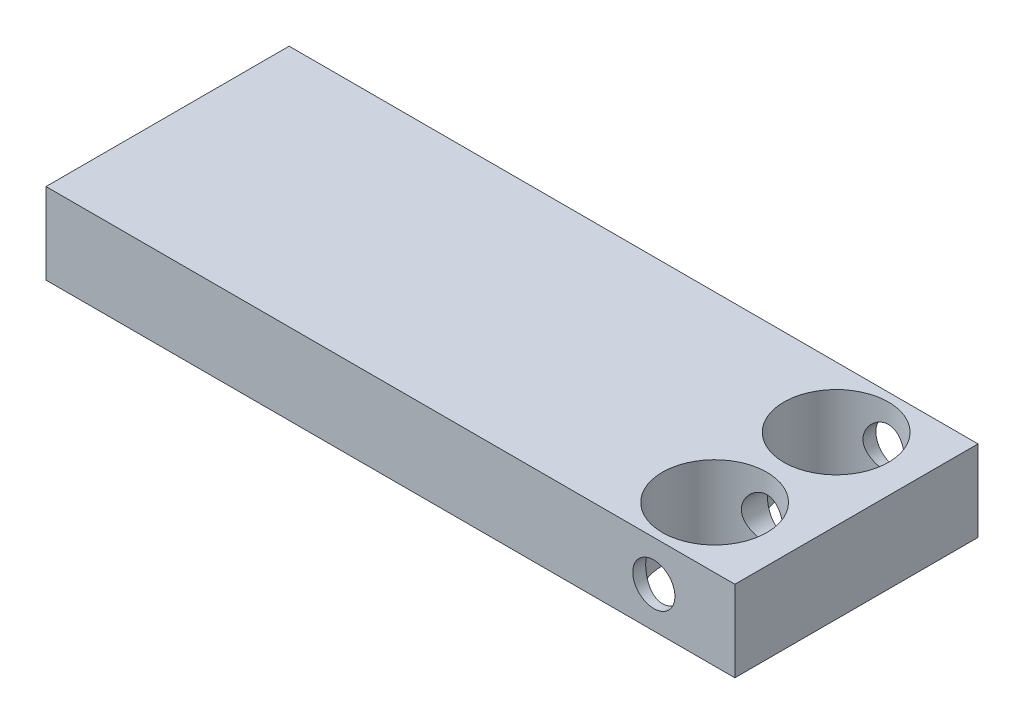
SolidWorks part; units mm, degrees
ref_plane "Front Plane" through (0, 0, 0) normal (0, 0, 1) x (1, 0, 0)
ref_plane "Top Plane" through (0, 0, 0) normal (0, 1, 0) x (1, 0, 0)
ref_plane "Right Plane" through (0, 0, 0) normal (1, 0, 0) x (0, 0, -1)
sketch "Sketch1" plane through (0, 0, 0) normal (0, 1, 0) x (1, 0, 0)
  line L1 (-39.5946, 7.7703) -> (45.4054, 7.7703)
  line L2 (-39.5946, 7.7703) -> (-39.5946, -22.2297)
  line L3 (-39.5946, -22.2297) -> (45.4054, -22.2297)
  line L4 (45.4054, 7.7703) -> (45.4054, -22.2297)
  circle A0 centre (35.4054, 0.2703) radius 6.45
  circle A1 centre (35.4054, -14.7297) radius 6.45
  dimension "D4" = 12.9
  dimension "D5" = 12.9
  dimension "D1" = 85
  dimension "D2" = 30
  dimension "D3" = 15
  dimension "D6" = 10
  dimension "D7" = 7.5
extrude "Boss-Extrude1" add sketch "Sketch1" along normal blind 10
sketch "Sketch2" plane through (0, 0, 22.2297) normal (0, 0, 1) x (1, 0, 0)
  line L0 (-39.5946, 10) -> (45.4054, 10) construction
  line L1 (45.4054, 10) -> (45.4054, 0) construction
  circle A0 centre (35.4054, 5) radius 2.6
  dimension "D3" = 5.2
  dimension "D1" = 5
  dimension "D2" = 10
extrude "Cut-Extrude1" cut sketch "Sketch2" against normal through all
